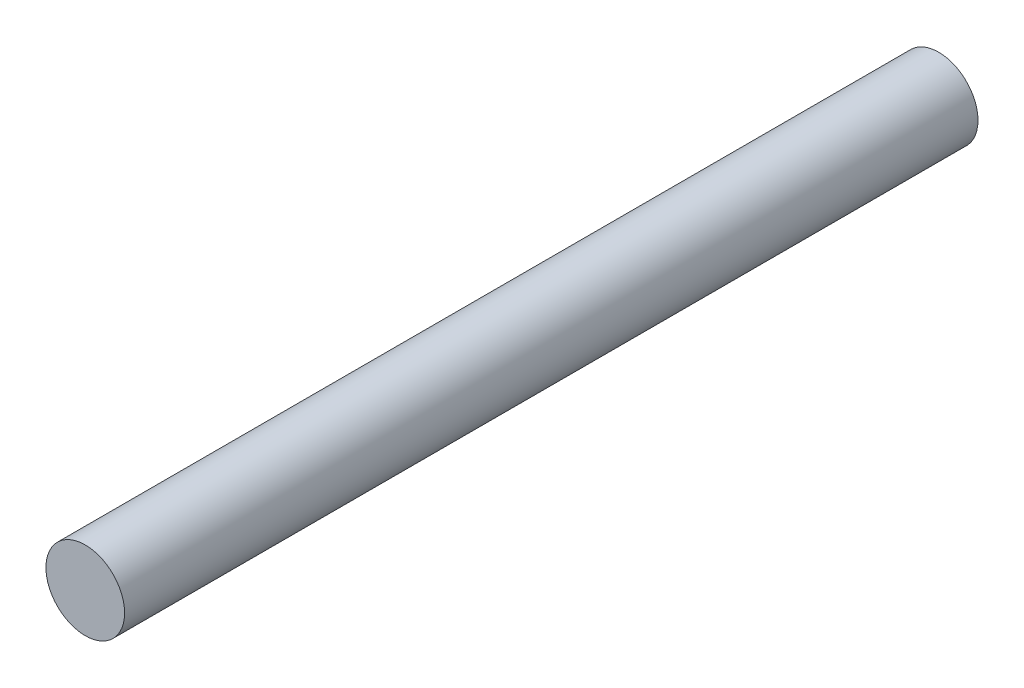
SolidWorks part; units mm, degrees
ref_plane "Front Plane" through (0, 0, 0) normal (0, 0, 1) x (1, 0, 0)
ref_plane "Top Plane" through (0, 0, 0) normal (0, 1, 0) x (1, 0, 0)
ref_plane "Right Plane" through (0, 0, 0) normal (1, 0, 0) x (0, 0, -1)
sketch "Sketch1" plane through (0, 0, 0) normal (0, 0, 1) x (1, 0, 0)
  circle A0 centre (0, 0) radius 2.5
extrude "Boss-Extrude1" add sketch "Sketch1" along normal blind 54.24
